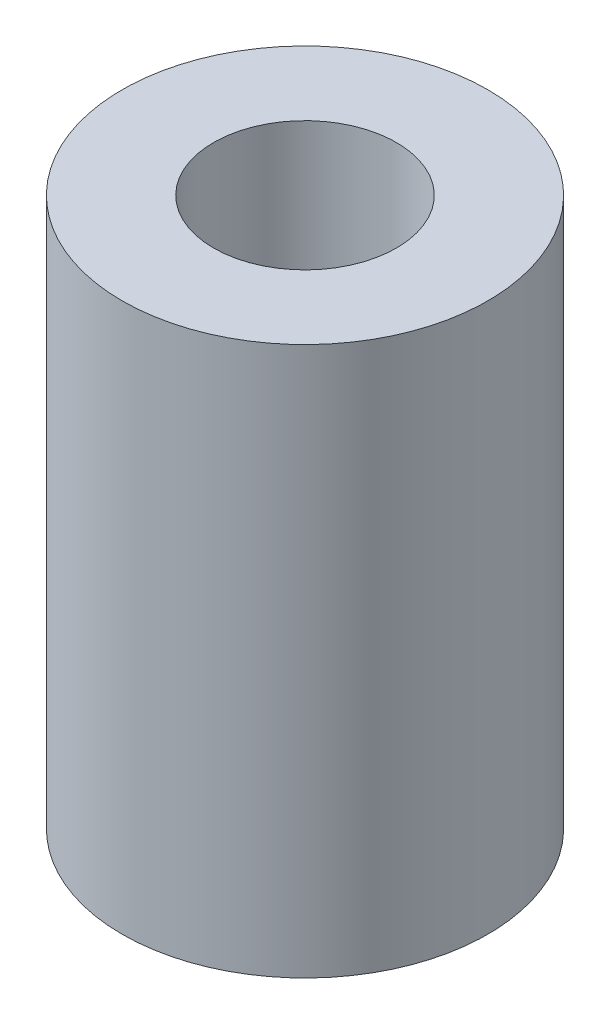
SolidWorks part; units mm, degrees
ref_plane "Front Plane" through (0, 0, 0) normal (0, 0, 1) x (1, 0, 0)
ref_plane "Top Plane" through (0, 0, 0) normal (0, 1, 0) x (1, 0, 0)
ref_plane "Right Plane" through (0, 0, 0) normal (1, 0, 0) x (0, 0, -1)
sketch "Sketch1" plane through (0, 0, 0) normal (0, 1, 0) x (1, 0, 0)
  circle A0 centre (0, 0) radius 6.35
  dimension "D1" = 12.7
extrude "Boss-Extrude1" add sketch "Sketch1" along normal blind 19.05
sketch "Sketch2" plane through (0, 19.05, 0) normal (0, 1, 0) x (1, 0, 0)
  circle A0 centre (0, 0) radius 3.175
  dimension "D1" = 6.35
extrude "Cut-Extrude1" cut sketch "Sketch2" against normal through all both and the other way through all
